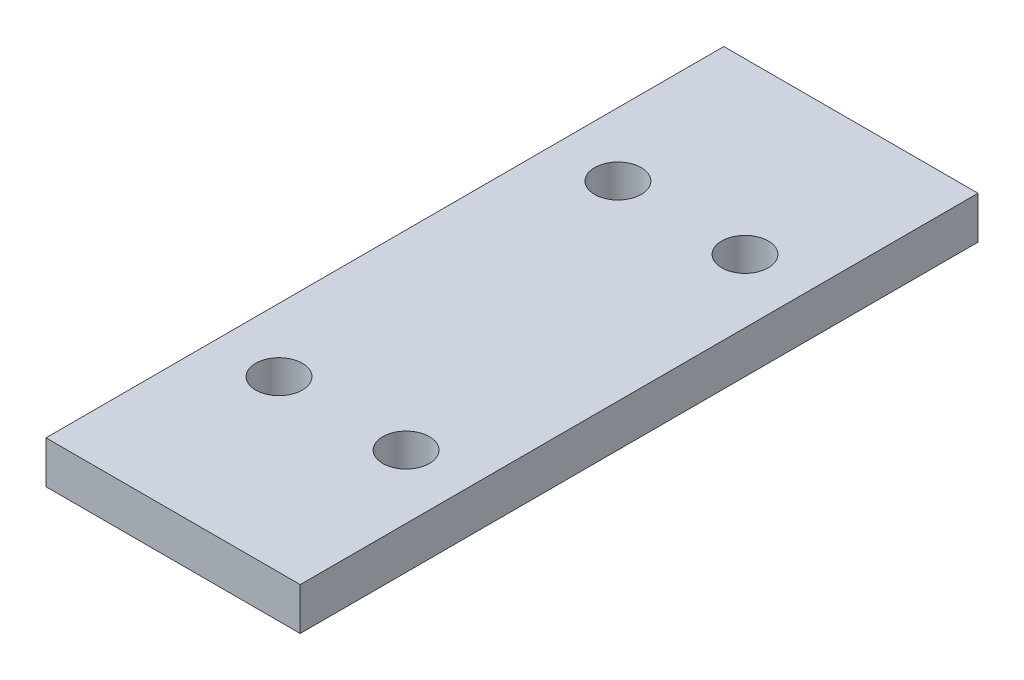
SolidWorks part; units mm, degrees
ref_plane "Front Plane" through (0, 0, 0) normal (0, 0, 1) x (1, 0, 0)
ref_plane "Top Plane" through (0, 0, 0) normal (0, 1, 0) x (1, 0, 0)
ref_plane "Right Plane" through (0, 0, 0) normal (1, 0, 0) x (0, 0, -1)
sketch "Sketch1" plane through (0, 0, 0) normal (0, 1, 0) x (1, 0, 0)
  line L1 (-19.05, 50.8) -> (19.05, 50.8)
  line L2 (-19.05, 50.8) -> (-19.05, -50.8)
  line L3 (-19.05, -50.8) -> (19.05, -50.8)
  line L4 (19.05, 50.8) -> (19.05, -50.8)
  line L5 (-19.05, 50.8) -> (19.05, -50.8) construction
  line L6 (-19.05, -50.8) -> (19.05, 50.8) construction
  line L7 (-9.525, 25.4) -> (9.525, 25.4) construction
  line L8 (-9.525, 25.4) -> (-9.525, -25.4) construction
  line L9 (-9.525, -25.4) -> (9.525, -25.4) construction
  line L10 (9.525, 25.4) -> (9.525, -25.4) construction
  line L11 (-9.525, 25.4) -> (9.525, -25.4) construction
  line L12 (-9.525, -25.4) -> (9.525, 25.4) construction
  circle A3 centre (-9.525, 25.4) radius 3.4925
  circle A4 centre (9.525, 25.4) radius 3.4925
  circle A5 centre (9.525, -25.4) radius 3.4925
  circle A6 centre (-9.525, -25.4) radius 3.4925
  point P0 (0, 0)
  point P6 (0, 0)
  dimension "D5" = 6.985
  dimension "D1" = 19.05
  dimension "D2" = 101.6
  dimension "D3" = 50.8
  dimension "D4" = 9.525
extrude "Boss-Extrude1" add sketch "Sketch1" along normal blind 6.35
